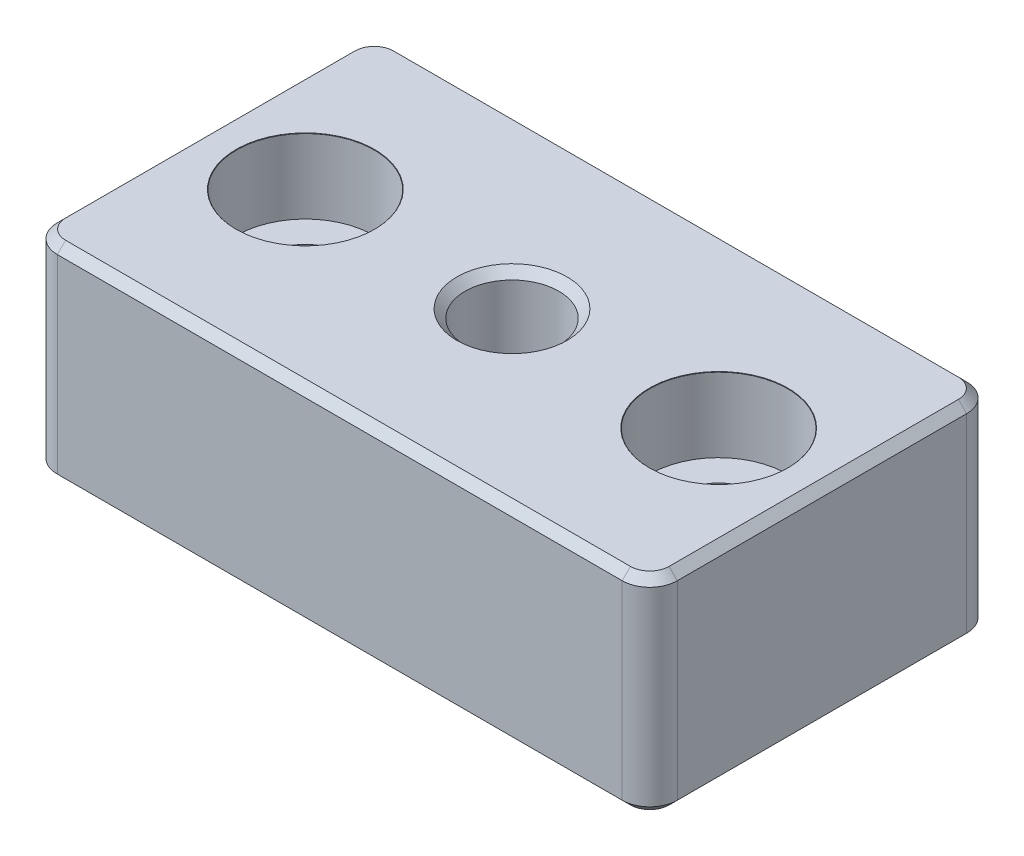
SolidWorks part; units mm, degrees
material "ABS"
ref_plane "Front Plane" through (0, 0, 0) normal (0, 0, 1) x (1, 0, 0)
ref_plane "Top Plane" through (0, 0, 0) normal (0, 1, 0) x (1, 0, 0)
ref_plane "Right Plane" through (0, 0, 0) normal (1, 0, 0) x (0, 0, -1)
sketch "Sketch1" plane through (0, 0, 0) normal (0, 1, 0) x (1, 0, 0)
  line L1 (22.5, -12.5) -> (-22.5, -12.5)
  line L2 (22.5, -12.5) -> (22.5, 12.5)
  line L3 (22.5, 12.5) -> (-22.5, 12.5)
  line L4 (-22.5, -12.5) -> (-22.5, 12.5)
  line L5 (22.5, -12.5) -> (-22.5, 12.5) construction
  line L6 (22.5, 12.5) -> (-22.5, -12.5) construction
  point P0 (0, 0)
  dimension "D1" = 45
  dimension "D2" = 25
extrude "Boss-Extrude1" add sketch "Sketch1" along normal blind 15
hole_wizard "Hole1" positions "Sketch2" profile "Sketch4" legacy
sketch "Sketch2" plane through (0, 15, 0) normal (0, 1, 0) x (1, 0, 0)
  point P0 (0, 0)
sketch "Sketch4" plane through (0, 15, 0) normal (1, 0, 0) x (0, 0, 1)
  line L0 (0, 0) -> (0, 10)
  line L1 (0, 10) -> (3.4, 10)
  line L2 (3.4, 10) -> (3.4, 0)
  line L3 (3.4, 0) -> (0, 0)
  line L4 (0, 110) -> (0, -10) construction
  dimension "Diameter" = 6.8
  dimension "Depth" = 10
hole_wizard "CBORE for M5 Hex Socket Head Cap Screw1" positions "Sketch5" profile "Sketch7" counterbore size "M5" standard "DIN" end condition up to next
sketch "Sketch5" plane through (0, 15, 0) normal (0, 1, 0) x (1, 0, 0)
  line L0 (0, 0) -> (0, 12.5) construction
  line L1 (22.5, 12.5) -> (-22.5, 12.5) construction
  line L2 (0, 0) -> (-15, 0) construction
  point P8 (-15, 0)
  point P10 (15, 0)
  dimension "D1" = 30
sketch "Sketch7" plane through (15, 15, 0) normal (1, 0, 0) x (0, 0, 1)
  line L0 (0, 0) -> (0, 15)
  line L1 (0, 15) -> (2.75, 15)
  line L3 (2.75, 15) -> (2.75, 5.4)
  line L4 (5, 5.4) -> (2.75, 5.4)
  line L5 (5, 5.4) -> (5, 0.025)
  line L6 (5, 0.025) -> (5.025, 0)
  line L7 (5.025, 0) -> (0, 0)
  line L8 (-5, 0.025) -> (-5.025, 0) construction
  line L11 (0, -6.35) -> (0, 107.95) construction
  dimension "Thru Hole Dia." = 5.5
  dimension "Thru Hole Depth" = 15
  dimension "C'Bore Dia." = 10
  dimension "C'Bore Depth" = 5.4
  dimension "Near C'Sink Dia." = 10.05
  dimension "Near C'Sink Angle" = 90
fillet "Fillet1" radius 2 4 edges at (-22.5, 7.5, -12.5) (-22.5, 7.5, 12.5) (22.5, 7.5, -12.5) (22.5, 7.5, 12.5)
chamfer "Chamfer1" distance 0.6 angle 45 19 edges at (-21.9142, 0, 11.9142) (0, 0, 12.5) (21.9142, 0, 11.9142) (22.5, 0, 0) (21.9142, 0, -11.9142) (0, 0, -12.5) (-21.9142, 0, -11.9142) (-22.5, 0, 0) (15, 0, 2.75) (-15, 0, 2.75) (0, 15, -12.5) (-21.9142, 15, -11.9142) (21.9142, 15, -11.9142) (-22.5, 15, 0) (22.5, 15, 0) (-21.9142, 15, 11.9142) (21.9142, 15, 11.9142) (0, 15, 12.5) (0, 15, 3.4)
